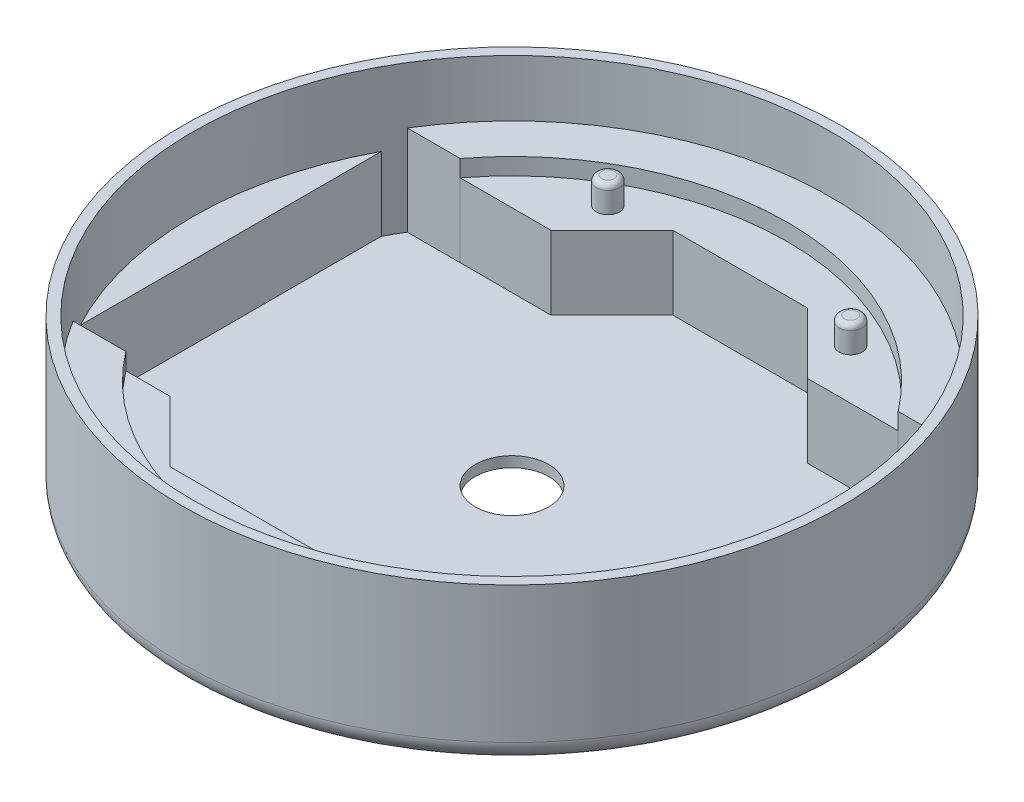
SolidWorks part; units mm, degrees
ref_plane "Front Plane" through (0, 0, 0) normal (0, 0, 1) x (1, 0, 0)
ref_plane "Top Plane" through (0, 0, 0) normal (0, 1, 0) x (1, 0, 0)
ref_plane "Right Plane" through (0, 0, 0) normal (1, 0, 0) x (0, 0, -1)
sketch "Sketch1" plane through (0, 0, 0) normal (0, 1, 0) x (1, 0, 0)
  circle A0 centre (0, 0) radius 31.4
  dimension "D1" = 62.8
extrude "Main Cylinder" add sketch "Sketch1" along normal blind 15
shell "Inner shell" thickness 1
fillet "Outer bottom edge" radius 2 1 edges at (0, 0, 31.4)
sketch "Sketch10" plane through (0, 1, 0) normal (0, 1, 0) x (-1, 0, 0)
  circle A0 centre (0, 0) radius 3.5
extrude "Bottom hole" cut sketch "Sketch10" against normal up to next
sketch "Reference" plane through (0, 1, 0) normal (0, 1, 0) x (-1, 0, 0)
  line L1 (26, 15.125) -> (-26, 15.125) construction
  line L2 (26, 15.125) -> (26, -15.125) construction
  line L3 (26, -15.125) -> (-26, -15.125) construction
  line L4 (-26, 15.125) -> (-26, -15.125) construction
  line L5 (26, 15.125) -> (-26, -15.125) construction
  line L6 (26, -15.125) -> (-26, 15.125) construction
  circle A0 centre (0, 0) radius 25.527 construction
  point P0 (0, 0)
  dimension "D1" = 52
  dimension "D2" = 30.25
sketch "Sketch12" plane through (0, 1, 0) normal (0, 1, 0) x (1, 0, 0)
  line L0 (-25.8951, 15.925) -> (-12.2173, 15.925)
  line L1 (-10.8458, -21.7332) -> (-16.654, -15.925)
  line L2 (-16.654, -15.925) -> (-25.8951, -15.925)
  line L3 (16.654, -15.925) -> (25.8951, -15.925)
  line L4 (-10.8458, -21.7332) -> (10.8458, -21.7332)
  line L5 (-26, 15.125) -> (26, 15.125) construction
  line L6 (10.8458, -21.7332) -> (16.654, -15.925)
  line L7 (-26, -15.125) -> (26, -15.125) construction
  line L8 (26.8, 14.3499) -> (26.8, -14.3499)
  line L9 (-26.8, 14.3499) -> (-26.8, -14.3499)
  line L10 (-26, -15.125) -> (-26, 15.125) construction
  line L11 (26, -15.125) -> (26, 15.125) construction
  line L12 (-12.2173, 15.925) -> (-6.4093, 21.733)
  line L13 (-6.4093, 21.733) -> (6.4093, 21.733)
  line L14 (0, 30.4) -> (0, -30.4) construction
  line L15 (12.2173, 15.925) -> (6.4093, 21.733)
  line L16 (25.8951, 15.925) -> (12.2173, 15.925)
  arc A0 (-25.8951, 15.925) -> (25.8951, 15.925) centre (0, 0) cw
  circle A1 centre (0, 0) radius 30.4 construction
  arc A2 (25.8951, -15.925) -> (-25.8951, -15.925) centre (0, 0) cw
  arc A4 (-26.8, 14.3499) -> (-26.8, -14.3499) centre (0, 0) ccw
  arc A5 (26.8, -14.3499) -> (26.8, 14.3499) centre (0, 0) ccw
  point P13 (0, -21.7332)
  point P30 (0, 0)
  point P34 (0, 21.733)
  dimension "D4" = 225
  dimension "D5" = 0.8
  dimension "D1" = 5.808
  dimension "D2" = 21.6916
  dimension "D3" = 0.8
  dimension "D6" = 0.8
  dimension "D7" = 135
  dimension "D8" = 0.8
extrude "Mounts" add sketch "Sketch12" along normal blind 7
sketch "Sketch14" plane through (0, 8, 0) normal (0, 1, 0) x (1, 0, 0)
  line L1 (-20.8676, 15.925) -> (-25.8951, 15.925)
  line L2 (-25.8951, 15.925) -> (-25.952, 15.8259)
  line L3 (20.8676, 15.925) -> (25.8951, 15.925)
  line L6 (12.2173, 15.925) -> (25.8951, 15.925) construction
  line L7 (-25.8951, 15.925) -> (-12.2173, 15.925) construction
  arc A0 (-25.8951, 15.925) -> (25.8951, 15.925) centre (0, 0) cw
  arc A1 (-20.8676, 15.925) -> (20.8676, 15.925) centre (0, 0) cw
  arc A2 (25.8951, 15.925) -> (-25.8951, 15.925) centre (0, 0) ccw construction
  dimension "D1" = 26.25
extrude "Holder (North)" add sketch "Sketch14" along normal blind 1.6 contours L1 A1 L3 A0
sketch "Sketch15" plane through (0, 8, 0) normal (0, 1, 0) x (1, 0, 0)
  line L0 (-20.8676, -15.925) -> (-25.8951, -15.925)
  line L1 (20.8676, -15.925) -> (25.8951, -15.925)
  line L2 (-16.654, -15.925) -> (-25.8951, -15.925) construction
  line L3 (25.8951, -15.925) -> (16.654, -15.925) construction
  arc A0 (-20.8676, -15.925) -> (20.8676, -15.925) centre (0, 0) ccw
  arc A1 (-25.8951, -15.925) -> (25.8951, -15.925) centre (0, 0) ccw
  arc A2 (-25.8951, -15.925) -> (25.8951, -15.925) centre (0, 0) ccw construction
  dimension "D1" = 26.25
extrude "Holder (South)" add sketch "Sketch15" along normal blind 1.6
sketch "Sketch17" plane through (0, 8, 0) normal (0, 1, 0) x (1, 0, 0)
  line L0 (0, 26.25) -> (0, -26.25) construction
  circle A0 centre (-11.56, 20.7) radius 1.1
  arc A1 (20.8676, 15.925) -> (-20.8676, 15.925) centre (0, 0) ccw construction
  arc A2 (-20.8676, -15.925) -> (20.8676, -15.925) centre (0, 0) ccw construction
  circle A3 centre (11.56, 20.7) radius 1.1
  dimension "D3" = 2.2
  dimension "D1" = 20.7
  dimension "D2" = 11.56
extrude "Boss-Extrude7" add sketch "Sketch17" along normal blind 2.5
fillet "Fillet1" radius 0.5 2 edges at (11.56, 10.5, -21.8) (-11.56, 10.5, -19.6)
sketch "Sketch18" plane through (0, 0, -15.925) normal (0, 0, 1) x (1, 0, 0)
  line L0 (-20.8676, 8) -> (-20.8676, 1)
  line L1 (-25.8951, 1) -> (-12.2173, 1) construction
split line "Split Line1"
sketch "Sketch19" plane through (0, 0, -15.925) normal (0, 0, 1) x (1, 0, 0)
  line L0 (20.8676, 8) -> (20.8676, 1)
  line L1 (12.2173, 1) -> (25.8951, 1) construction
split line "Split Line2"
